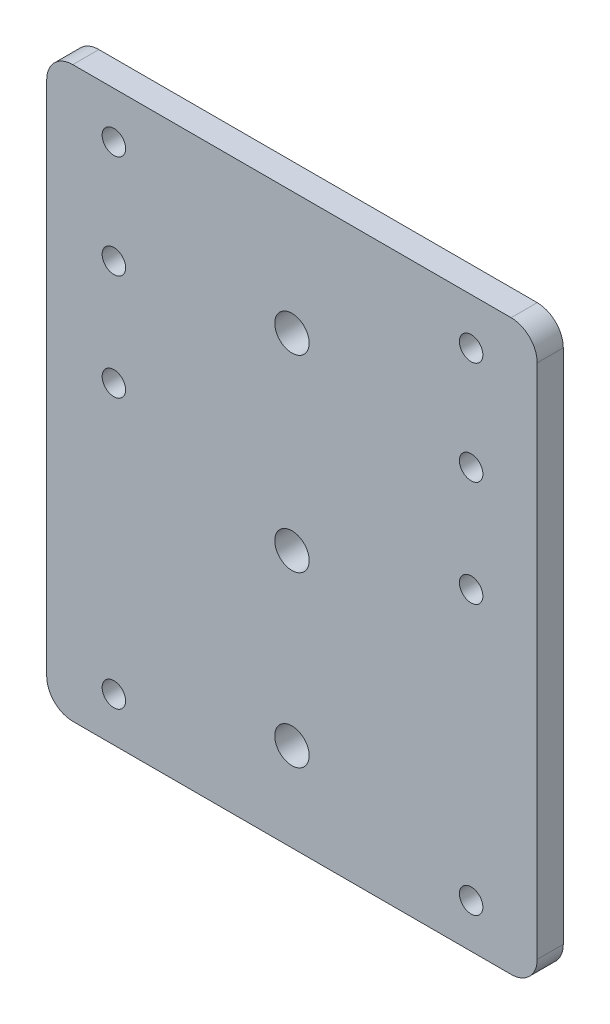
SolidWorks part; units mm, degrees
ref_plane "Plan de face" through (0, 0, 0) normal (0, 0, 1) x (1, 0, 0)
ref_plane "Plan de dessus" through (0, 0, 0) normal (0, 1, 0) x (1, 0, 0)
ref_plane "Plan de droite" through (0, 0, 0) normal (1, 0, 0) x (0, 0, -1)
sketch "Esquisse1" plane through (0, 0, 0) normal (0, 0, 1) x (1, 0, 0)
  line L1 (-42, 54.5) -> (42, 54.5)
  line L2 (-47, 49.5) -> (-47, -49.5)
  line L3 (-42, -54.5) -> (42, -54.5)
  line L4 (47, 49.5) -> (47, -49.5)
  line L5 (-47, 54.5) -> (47, -54.5) construction
  line L6 (-47, -54.5) -> (47, 54.5) construction
  arc A0 (42, -54.5) -> (47, -49.5) centre (42, -49.5) ccw
  arc A1 (-42, -54.5) -> (-47, -49.5) centre (-42, -49.5) cw
  arc A2 (-47, 49.5) -> (-42, 54.5) centre (-42, 49.5) cw
  arc A3 (47, 49.5) -> (42, 54.5) centre (42, 49.5) ccw
  point P0 (0, 0)
  dimension "D3" = 5
  dimension "D1" = 109
  dimension "D2" = 94
extrude "Boss.-Extru.1" add sketch "Esquisse1" along normal blind 5
hole_wizard "Dégagement M61" positions "Esquisse3" profile "Esquisse2" hole size "M6" standard "JIS" end condition through all
sketch "Esquisse3" plane through (0, 0, 5) normal (0, 0, 1) x (1, 0, 0)
  point P0 (0, 30.9294)
  point P2 (0, -37.545)
  point P4 (0, -5.1583)
sketch "Esquisse2" plane through (0, 30.9294, 5) normal (1, 0, 0) x (0, -1, 0)
  line L0 (0, 0) -> (0, 5)
  line L1 (0, 5) -> (3.3, 5)
  line L2 (3.3, 5) -> (3.3, 0)
  line L5 (3.3, 0) -> (0, 0)
  line L11 (0, -6.35) -> (0, 107.95) construction
  dimension "Diamètre du perçage jusqu'au prochain" = 6.6
  dimension "Profondeur du perçage jusqu'au prochain" = 5
hole_wizard "Dégagement M41" positions "Esquisse5" profile "Esquisse4" hole size "M4" standard "JIS" end condition through all
sketch "Esquisse5" plane through (0, 0, 5) normal (0, 0, 1) x (1, 0, 0)
  point P0 (34.3362, 45.6113)
  point P2 (34.3362, 25.8445)
  point P4 (34.3362, 5.5727)
  point P6 (34.3362, -46.0462)
  point P8 (-34.1252, -46.0462)
  point P10 (-34.1252, 5.5727)
  point P12 (-34.1252, 25.8445)
  point P14 (-34.1252, 45.6113)
sketch "Esquisse4" plane through (34.3362, 45.6113, 5) normal (1, 0, 0) x (0, -1, 0)
  line L0 (0, 0) -> (0, 5)
  line L1 (0, 5) -> (2.25, 5)
  line L2 (2.25, 5) -> (2.25, 0)
  line L5 (2.25, 0) -> (0, 0)
  line L11 (0, -6.35) -> (0, 107.95) construction
  dimension "Diamètre du perçage jusqu'au prochain" = 4.5
  dimension "Profondeur du perçage jusqu'au prochain" = 5
